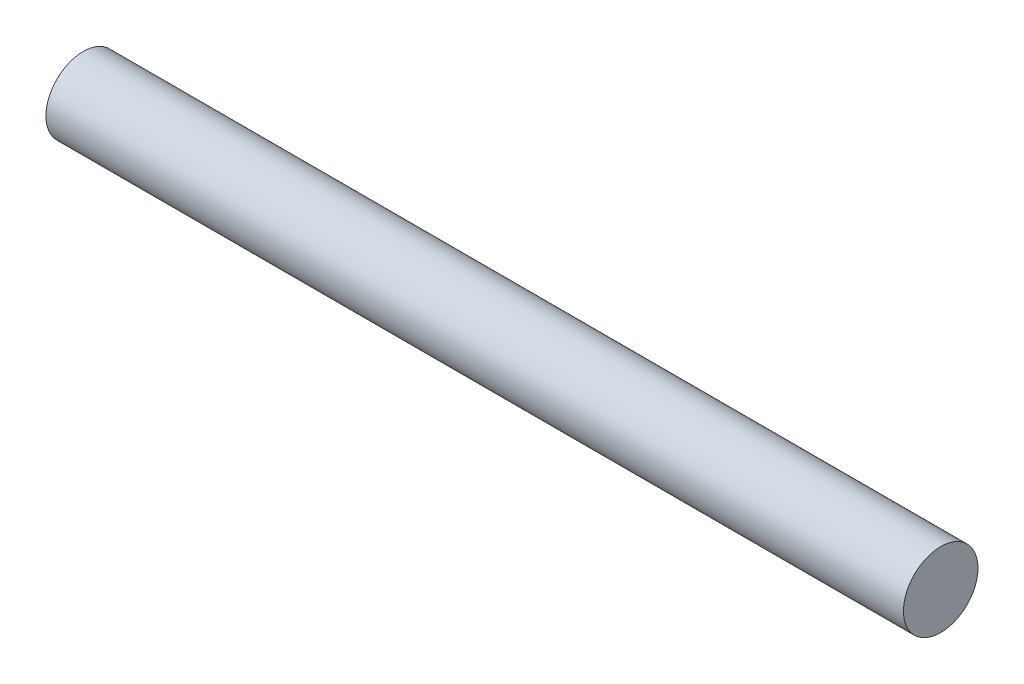
SolidWorks part; units mm, degrees
material "PETG"
ref_plane "Front Plane" through (0, 0, 0) normal (0, 0, 1) x (1, 0, 0)
ref_plane "Top Plane" through (0, 0, 0) normal (0, 1, 0) x (1, 0, 0)
ref_plane "Right Plane" through (0, 0, 0) normal (1, 0, 0) x (0, 0, -1)
sketch "Sketch1" plane through (0, 0, 0) normal (1, 0, 0) x (0, 0, -1)
  circle A0 centre (0, 0) radius 1
  dimension "D1" = 2
extrude "Boss-Extrude1" add sketch "Sketch1" along normal blind 23
ref_plane "Plane1" through (11.5, 0, 0) normal (1, 0, 0) x (0, 0, -1)
scale "Scale1" scale about origin uniform scaling yes scale factor 1
